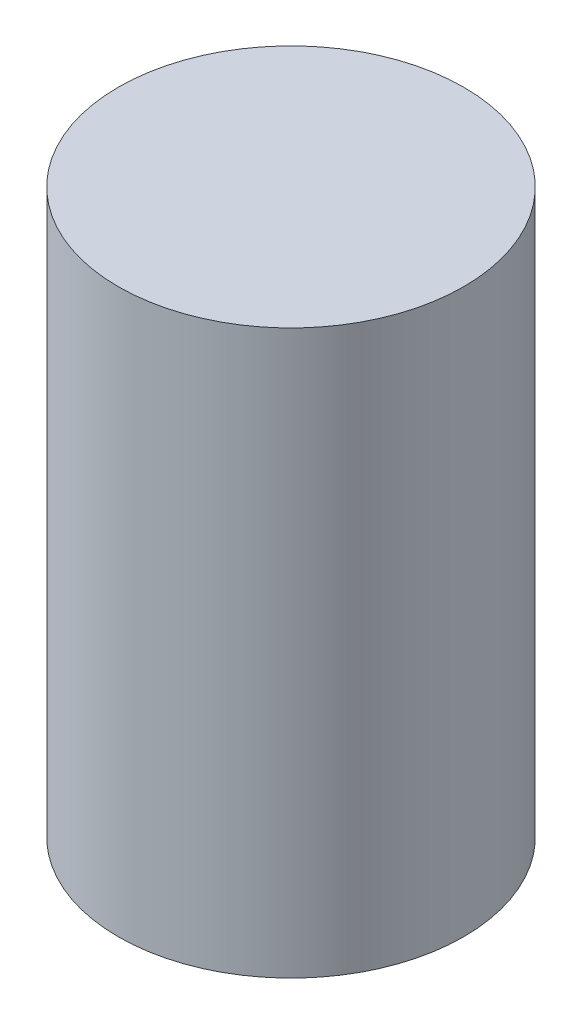
SolidWorks part; units mm, degrees
ref_plane "Front Plane" through (0, 0, 0) normal (0, 0, 1) x (1, 0, 0)
ref_plane "Top Plane" through (0, 0, 0) normal (0, 1, 0) x (1, 0, 0)
ref_plane "Right Plane" through (0, 0, 0) normal (1, 0, 0) x (0, 0, -1)
sketch "Sketch1" plane through (0, 0, 0) normal (0, 1, 0) x (1, 0, 0)
  circle A0 centre (0, 0) radius 85.725
  dimension "D1" = 171.45
extrude "Boss-Extrude1" add sketch "Sketch1" along normal blind 279.4
